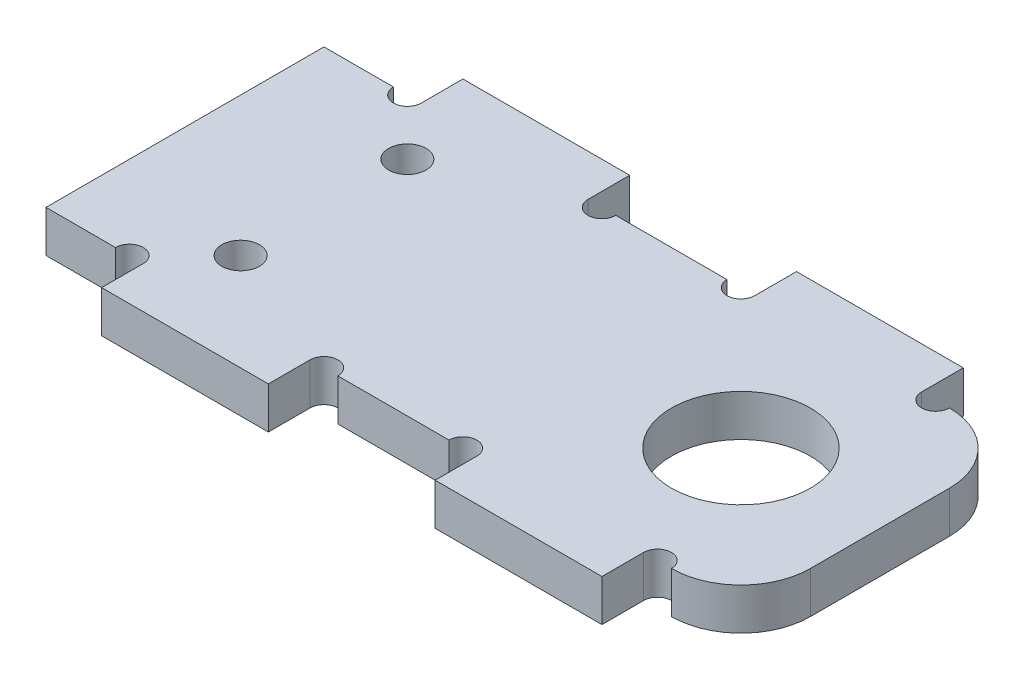
SolidWorks part; units mm, degrees
material "碳纤维"
ref_plane "前视基准面" through (0, 0, 0) normal (0, 0, 1) x (1, 0, 0)
ref_plane "上视基准面" through (0, 0, 0) normal (0, 1, 0) x (1, 0, 0)
ref_plane "右视基准面" through (0, 0, 0) normal (1, 0, 0) x (0, 0, -1)
sketch "草图1" plane through (0, 0, 0) normal (0, 1, 0) x (1, 0, 0)
  line L0 (-30, 10) -> (-30, -10) construction
  line L1 (-10, -10) -> (10, -10)
  line L3 (-10, 10) -> (10, 10)
  line L4 (10, -10) -> (10, 10)
  line L5 (0, 10) -> (0, -10) construction
  line L6 (-10, 0) -> (10, 0) construction
  line L7 (-10, 10) -> (-30, 10)
  line L9 (-10, -10) -> (-30, -10)
  line L11 (-30, 10) -> (-40, 10)
  line L12 (-40, 10) -> (-40, -10)
  line L13 (-40, -10) -> (-30, -10)
  circle A0 centre (0, 0) radius 5
  circle A5 centre (-30, -6) radius 1.35
  circle A6 centre (-30, 6) radius 1.35
  point P0 (0, 0)
  dimension "D1" = 10
  dimension "D4" = 2.7
  dimension "D5" = 12
  dimension "D2" = 20
  dimension "D3" = 10
  dimension "D7" = 30
  dimension "D8" = 10
extrude "凸台-拉伸1" add sketch "草图1" along normal blind 3
fillet "圆角1" radius 5 2 edges at (10, 1.5, -10) (10, 1.5, 10)
sketch "草图3" plane through (0, 0, 0) normal (0, -1, 0) x (1, 0, 0)
  line L0 (-15, 10) -> (-15, -10) construction
  line L1 (-40, 10) -> (5, 10) construction
  line L3 (3, 13) -> (-9, 13)
  line L4 (-33, 10) -> (-21, 10)
  line L5 (-33, 10) -> (-33, 13)
  line L6 (-33, 13) -> (-21, 13)
  line L7 (-21, 10) -> (-21, 13)
  line L8 (-27, 13) -> (-27, 10) construction
  line L9 (-33, 11.5) -> (-21, 11.5) construction
  line L10 (-9, 10) -> (-9, 13)
  line L11 (3, 10) -> (-9, 10)
  line L12 (3, 10) -> (3, 13)
  line L13 (0, 0) -> (-15, 0) construction
  line L14 (3, -10) -> (3, -13)
  line L15 (3, -10) -> (-9, -10)
  line L16 (-9, -10) -> (-9, -13)
  line L17 (3, -13) -> (-9, -13)
  line L18 (-33, -13) -> (-21, -13)
  line L19 (-21, -10) -> (-21, -13)
  line L20 (-33, -10) -> (-21, -10)
  line L21 (-33, -10) -> (-33, -13)
  line L22 (-40, -10) -> (-40, 10) construction
  point P24 (0, 0)
  point P25 (0, 0)
  point P26 (0, 0)
  point P27 (-20, 10)
  point P146 (-27, 11.5)
  dimension "D1" = 12
  dimension "D2" = 3
  dimension "D3" = 12
  dimension "D4" = 25
extrude "凸台-拉伸2" add sketch "草图3" against normal up to surface (3 mm away) up to face at (-7.9882, 3, 0)
sketch "草图4" plane through (0, 0, 0) normal (0, -1, 0) x (1, 0, 0)
  line L0 (-40, 10) -> (-33, 10) construction
  line L1 (-27, 13) -> (-27, 6) construction
  line L2 (-21, 13) -> (-33, 13) construction
  line L3 (-15, 10) -> (-15, -10) construction
  line L4 (-21, 10) -> (-9, 10) construction
  line L5 (-9, -10) -> (-21, -10) construction
  line L6 (0, 0) -> (-40, 0) construction
  line L7 (-40, -10) -> (-40, 10) construction
  circle A0 centre (-34, 10) radius 1
  circle A1 centre (-20, 10) radius 1
  circle A2 centre (-10, 10) radius 1
  circle A3 centre (4, 10) radius 1
  circle A4 centre (4, -10) radius 1
  circle A5 centre (-10, -10) radius 1
  circle A6 centre (-20, -10) radius 1
  circle A7 centre (-34, -10) radius 1
  dimension "D1" = 2
extrude "切除-拉伸1" cut sketch "草图4" against normal through all
